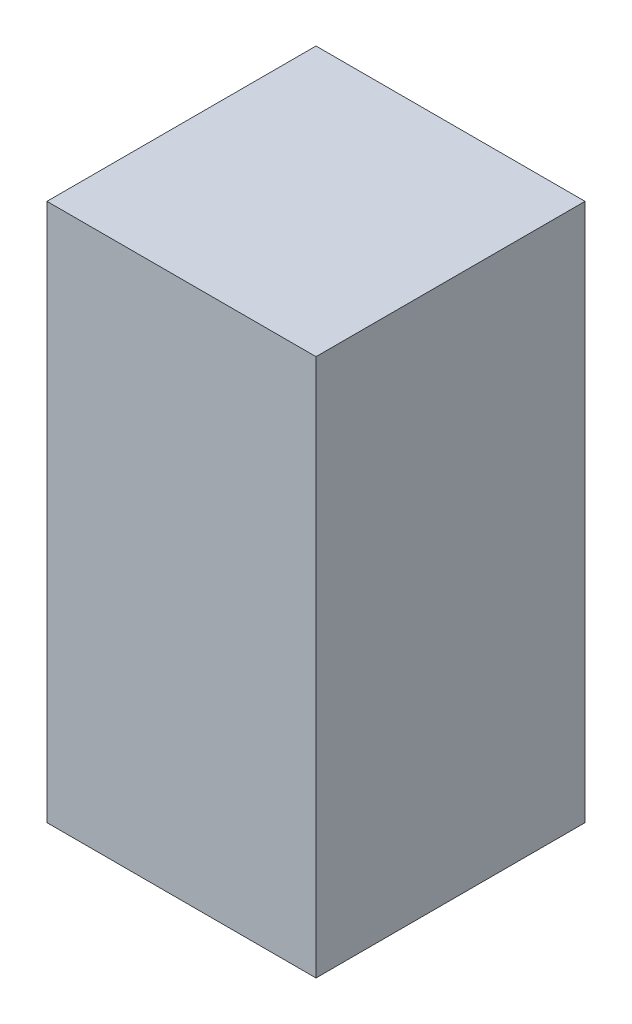
SolidWorks part; units mm, degrees
ref_plane "Front Plane" through (0, 0, 0) normal (0, 0, 1) x (1, 0, 0)
ref_plane "Top Plane" through (0, 0, 0) normal (0, 1, 0) x (1, 0, 0)
ref_plane "Right Plane" through (0, 0, 0) normal (1, 0, 0) x (0, 0, -1)
sketch "Sketch1" plane through (0, 0, 0) normal (0, 0, 1) x (1, 0, 0)
  line L1 (0, 0) -> (12.7, 0)
  line L2 (0, 0) -> (0, 25.4)
  line L3 (0, 25.4) -> (12.7, 25.4)
  line L4 (12.7, 0) -> (12.7, 25.4)
  dimension "D1" = 25.4
  dimension "D2" = 12.7
extrude "Boss-Extrude1" add sketch "Sketch1" along normal blind 12.7
